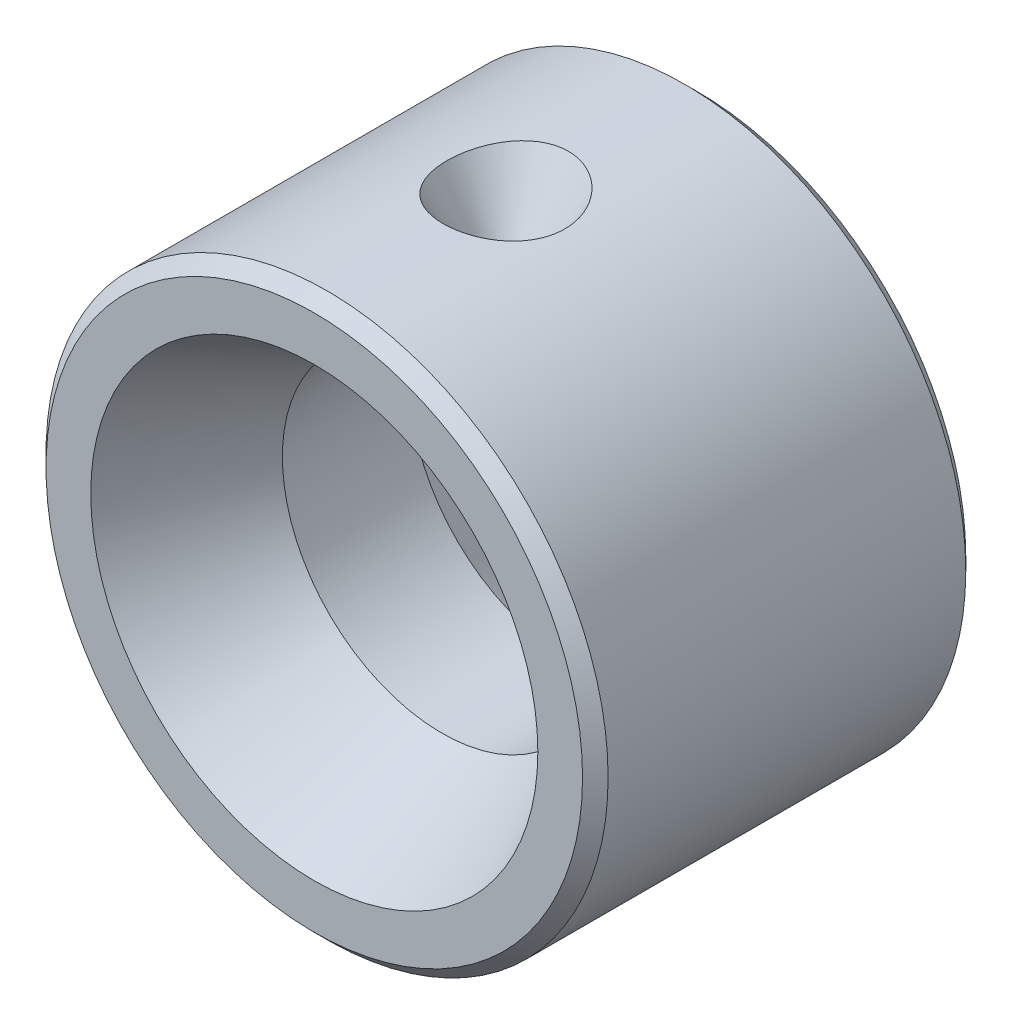
SolidWorks part; units mm, degrees
material "PE High Density"
ref_plane "Front Plane" through (0, 0, 0) normal (0, 0, 1) x (1, 0, 0)
ref_plane "Top Plane" through (0, 0, 0) normal (0, 1, 0) x (1, 0, 0)
ref_plane "Right Plane" through (0, 0, 0) normal (1, 0, 0) x (0, 0, -1)
sketch "Sketch1" plane through (0, 0, 0) normal (0, 0, 1) x (1, 0, 0)
  circle A0 centre (0, 0) radius 12.5
  circle A1 centre (0, 0) radius 22
  dimension "D1" = 25
  dimension "D2" = 44
extrude "Boss-Extrude1" add sketch "Sketch1" along normal mid plane 30
chamfer "Chamfer1" distance 1 angle 45 2 edges at (22, 0, -15) (22, 0, 15)
chamfer "Chamfer2" distance 5 distance2 10 1 edges at (12.5, 0, 15)
chamfer "Chamfer3" distance 10 distance2 5 1 edges at (12.5, 0, -15)
revolve "Cut-Revolve1" cut sketch "Sketch2" angle 360 about L0
sketch "Sketch2" plane through (-103.1364, -329.9949, 0) normal (0, 0, 1) x (-1, 0, 0)
  line L0 (-103.1364, -304.9949) -> (-103.1364, -316.4949)
  line L2 (-103.1364, -316.4949) -> (-96.4969, -304.9949)
  line L3 (-96.4969, -304.9949) -> (-103.1364, -304.9949)
mirror "Mirror3" about plane through (0, 0, 0) normal (0, 1, 0) of "Cut-Revolve1"
